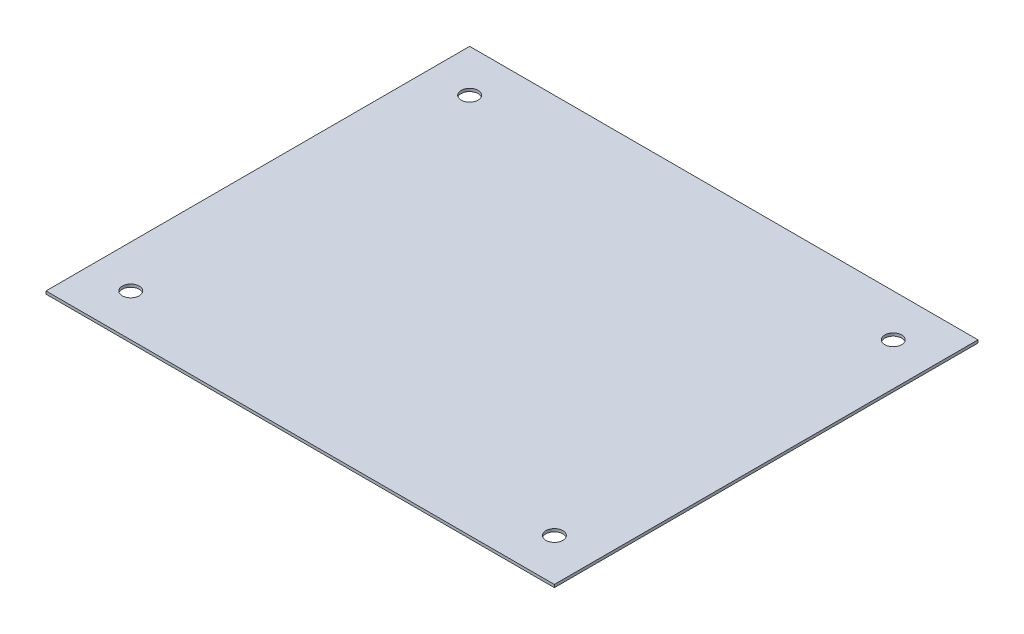
SolidWorks part; units mm, degrees
material "BUTİL"
ref_plane "Ön Düzlem" through (0, 0, 0) normal (0, 0, 1) x (1, 0, 0)
ref_plane "Üst Düzlem" through (0, 0, 0) normal (0, 1, 0) x (1, 0, 0)
ref_plane "Sağ Düzlem" through (0, 0, 0) normal (1, 0, 0) x (0, 0, -1)
sketch "Çizim1" plane through (0, 0, 0) normal (0, 1, 0) x (1, 0, 0)
  line L1 (-90, 75) -> (90, 75)
  line L2 (-90, 75) -> (-90, -75)
  line L3 (-90, -75) -> (90, -75)
  line L4 (90, 75) -> (90, -75)
  line L5 (-90, 75) -> (90, -75) construction
  line L6 (-90, -75) -> (90, 75) construction
  point P0 (0, 0)
  dimension "D1" = 150
  dimension "D2" = 180
extrude "Yükseklik-Ekstrüzyon1" add sketch "Çizim1" along normal blind 1
sketch "Çizim2" plane through (0, 1, 0) normal (0, 1, 0) x (1, 0, 0)
  line L0 (0, 76.2144) -> (0, -76.2144) construction
  line L1 (-106.675, 0) -> (106.675, 0) construction
  line L2 (-90, 75) -> (-90, -75) construction
  line L3 (90, 75) -> (-90, 75) construction
  circle A1 centre (-75, 60) radius 3
  circle A2 centre (75, 60) radius 3
  circle A3 centre (75, -60) radius 3
  circle A4 centre (-75, -60) radius 3
  point P4 (0, 0)
  point P10 (0, 0)
  dimension "D1" = 6
  dimension "D2" = 15
  dimension "D3" = 15
extrude "Kes-Ekstrüzyon1" cut sketch "Çizim2" against normal mid plane 50
